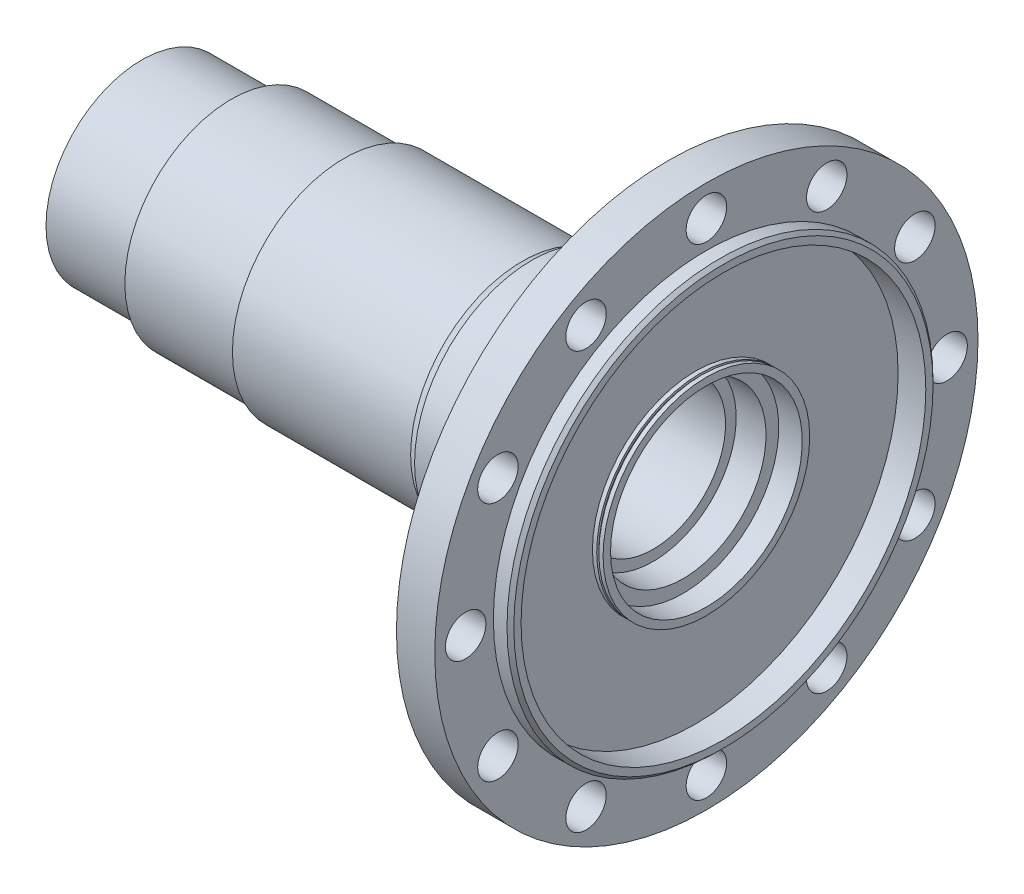
SolidWorks part; units mm, degrees
ref_plane "Спереди" through (0, 0, 0) normal (0, 0, 1) x (1, 0, 0)
ref_plane "Сверху" through (0, 0, 0) normal (0, 1, 0) x (1, 0, 0)
ref_plane "Справа" through (0, 0, 0) normal (1, 0, 0) x (0, 0, -1)
sketch "Эскиз1" plane through (0, 0, 0) normal (0, 0, 1) x (1, 0, 0)
  line L0 (0, 0) -> (273, 0)
  line L1 (0, 0) -> (0, 45)
  line L2 (0, 45) -> (42, 45)
  line L3 (42, 45) -> (42, 50)
  line L4 (42, 50) -> (95, 50)
  line L5 (95, 50) -> (95, 52.5)
  line L6 (95, 52.5) -> (178.6699, 52.5)
  line L7 (178.6699, 52.5) -> (183, 55)
  line L8 (183, 55) -> (215, 55)
  line L9 (215, 55) -> (215, 62.5)
  line L10 (215, 62.5) -> (239, 62.5)
  line L11 (239, 62.5) -> (239, 100)
  line L12 (239, 100) -> (247, 100)
  line L13 (247, 100) -> (247, 127.5)
  line L14 (247, 127.5) -> (265, 127.5)
  line L15 (265, 127.5) -> (265, 100)
  line L16 (265, 100) -> (271.4, 100)
  line L17 (271.4, 100) -> (273, 98.4)
  line L18 (273, 98.4) -> (273, 0)
revolve "Повернуть1" add sketch "Эскиз1" angle 360 about L0
sketch "Эскиз2" plane through (0, 0, 0) normal (0, 0, 1) x (1, 0, 0)
  line L0 (0, 0) -> (273, 0)
  line L1 (0, 0) -> (0, 31)
  line L2 (0, 31) -> (203.5, 31)
  line L3 (203.5, 31) -> (203.5, 34)
  line L4 (203.5, 34) -> (240, 34)
  line L5 (240, 34) -> (240, 39)
  line L6 (240, 39) -> (254, 39)
  line L7 (254, 39) -> (254, 45)
  line L8 (254, 45) -> (265, 45)
  line L9 (265, 45) -> (265, 95)
  line L10 (265, 95) -> (273, 95)
  line L11 (273, 95) -> (273, 0)
revolve "Вырез-Повернуть1" cut sketch "Эскиз2" angle 360 about L0
sketch "Эскиз3" plane through (0, 0, 0) normal (0, 0, 1) x (1, 0, 0)
  line L0 (0, 0) -> (273, 0) construction
  line L1 (260, 48.5) -> (262, 48.5)
  line L2 (262, 48.5) -> (262, 95)
  line L3 (262, 95) -> (260, 95)
  line L4 (260, 95) -> (260, 48.5)
revolve "Rear_recess_left" cut sketch "Эскиз3" angle 360 about L0
sketch "Эскиз4" plane through (0, 0, 0) normal (0, 0, 1) x (1, 0, 0)
  line L0 (0, 0) -> (273, 0) construction
  line L1 (262, 47.5) -> (263, 47.5)
  line L2 (263, 47.5) -> (263, 95)
  line L3 (263, 95) -> (262, 95)
  line L4 (262, 95) -> (262, 47.5)
revolve "Collar_groove_nominal" cut sketch "Эскиз4" angle 360 about L0
sketch "Эскиз5" plane through (0, 0, 0) normal (0, 0, 1) x (1, 0, 0)
  line L0 (0, 0) -> (273, 0) construction
  line L1 (263, 48.5) -> (265, 48.5)
  line L2 (265, 48.5) -> (265, 95)
  line L3 (265, 95) -> (263, 95)
  line L4 (263, 95) -> (263, 48.5)
revolve "Rear_recess_lip" cut sketch "Эскиз5" angle 360 about L0
sketch "Эскиз6" plane through (0, 0, 0) normal (1, 0, 0) x (0, 0, -1)
  circle A0 centre (0, 113) radius 9.5
extrude "Вырез-Вытянуть1" cut sketch "Эскиз6" along normal through all
sketch "Эскиз7" plane through (0, 0, 0) normal (1, 0, 0) x (0, 0, -1)
  circle A0 centre (-56.5, 97.8609) radius 9.5
extrude "Вырез-Вытянуть2" cut sketch "Эскиз7" along normal through all
sketch "Эскиз8" plane through (0, 0, 0) normal (1, 0, 0) x (0, 0, -1)
  circle A0 centre (-97.8609, 56.5) radius 9.5
extrude "Вырез-Вытянуть3" cut sketch "Эскиз8" along normal through all
sketch "Эскиз9" plane through (0, 0, 0) normal (1, 0, 0) x (0, 0, -1)
  circle A0 centre (-113, 0) radius 9.5
extrude "Вырез-Вытянуть4" cut sketch "Эскиз9" along normal through all
sketch "Эскиз10" plane through (0, 0, 0) normal (1, 0, 0) x (0, 0, -1)
  circle A0 centre (-97.8609, -56.5) radius 9.5
extrude "Вырез-Вытянуть5" cut sketch "Эскиз10" along normal through all
sketch "Эскиз11" plane through (0, 0, 0) normal (1, 0, 0) x (0, 0, -1)
  circle A0 centre (-56.5, -97.8609) radius 9.5
extrude "Вырез-Вытянуть6" cut sketch "Эскиз11" along normal through all
sketch "Эскиз12" plane through (0, 0, 0) normal (1, 0, 0) x (0, 0, -1)
  circle A0 centre (0, -113) radius 9.5
extrude "Вырез-Вытянуть7" cut sketch "Эскиз12" along normal through all
sketch "Эскиз13" plane through (0, 0, 0) normal (1, 0, 0) x (0, 0, -1)
  circle A0 centre (56.5, -97.8609) radius 9.5
extrude "Вырез-Вытянуть8" cut sketch "Эскиз13" along normal through all
sketch "Эскиз14" plane through (0, 0, 0) normal (1, 0, 0) x (0, 0, -1)
  circle A0 centre (97.8609, -56.5) radius 9.5
extrude "Вырез-Вытянуть9" cut sketch "Эскиз14" along normal through all
sketch "Эскиз15" plane through (0, 0, 0) normal (1, 0, 0) x (0, 0, -1)
  circle A0 centre (113, 0) radius 9.5
extrude "Вырез-Вытянуть10" cut sketch "Эскиз15" along normal through all
sketch "Эскиз16" plane through (0, 0, 0) normal (1, 0, 0) x (0, 0, -1)
  circle A0 centre (97.8609, 56.5) radius 9.5
extrude "Вырез-Вытянуть11" cut sketch "Эскиз16" along normal through all
sketch "Эскиз17" plane through (0, 0, 0) normal (1, 0, 0) x (0, 0, -1)
  circle A0 centre (56.5, 97.8609) radius 9.5
extrude "Вырез-Вытянуть12" cut sketch "Эскиз17" along normal through all
